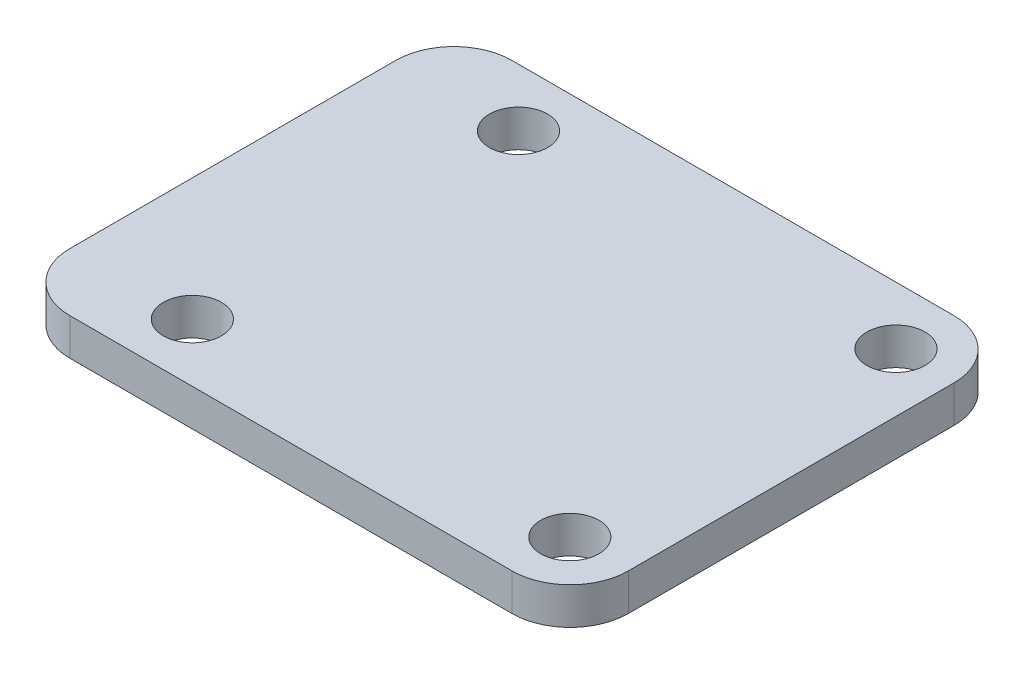
SolidWorks part; units mm, degrees
ref_plane "Front Plane" through (0, 0, 0) normal (0, 0, 1) x (1, 0, 0)
ref_plane "Top Plane" through (0, 0, 0) normal (0, 1, 0) x (1, 0, 0)
ref_plane "Right Plane" through (0, 0, 0) normal (1, 0, 0) x (0, 0, -1)
sketch "Sketch1" plane through (0, 0, 0) normal (0, 1, 0) x (1, 0, 0)
  line L1 (-12, -9.5) -> (12, -9.5)
  line L2 (-12, -9.5) -> (-12, 9.5)
  line L3 (-12, 9.5) -> (12, 9.5)
  line L4 (12, -9.5) -> (12, 9.5)
  line L5 (-12, -9.5) -> (12, 9.5) construction
  line L6 (-12, 9.5) -> (12, -9.5) construction
  point P0 (0, 0)
  dimension "D1" = 24
  dimension "D2" = 19
extrude "Boss-Extrude1" add sketch "Sketch1" along normal blind 1.5875
fillet "Fillet1" radius 2.5 4 edges at (12, 0.7937, -9.5) (-12, 0.7937, -9.5) (12, 0.7937, 9.5) (-12, 0.7937, 9.5)
sketch "Sketch2" plane through (0, 1.5875, 0) normal (0, 1, 0) x (1, 0, 0)
  line L0 (-6.7419, -5.7465) -> (-6.7419, -4.1834) construction
  line L1 (-5.4919, -6.9965) -> (-2.7889, -6.9965) construction
  line L2 (9.4823, -5.7465) -> (9.4823, -1.831) construction
  line L3 (-5.4919, 7.0208) -> (-3.6377, 7.0208) construction
  circle A0 centre (-6.7419, 7.0208) radius 1.25
  circle A1 centre (9.4823, 7.0208) radius 1.25
  circle A2 centre (9.4823, -6.9965) radius 1.25
  circle A3 centre (-6.7419, -6.9965) radius 1.25
  point P16 (0, 0)
  point P17 (0, 0)
  point P18 (0, 0)
  point P19 (0, 0)
  dimension "D1" = 2.5
  dimension "D2" = 2.5
  dimension "D3" = 2.5
  dimension "D4" = 2.5
extrude "Cut-Extrude1" cut sketch "Sketch2" against normal through all
